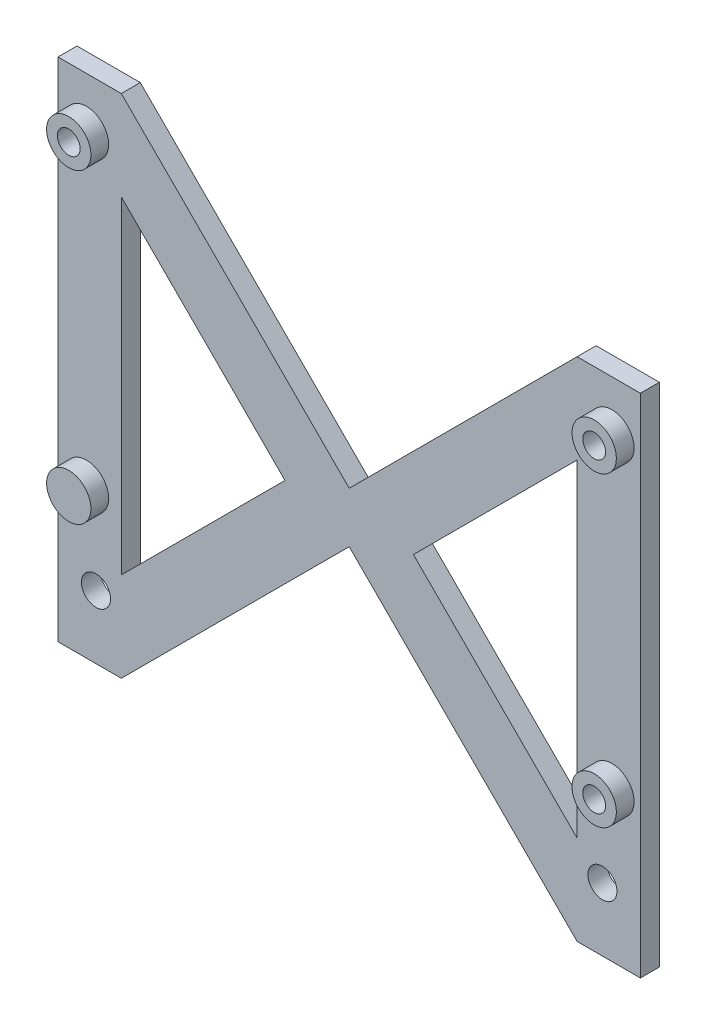
SolidWorks part; units mm, degrees
material "ABS"
ref_plane "Front Plane" through (0, 0, 0) normal (0, 0, 1) x (1, 0, 0)
ref_plane "Top Plane" through (0, 0, 0) normal (0, 1, 0) x (1, 0, 0)
ref_plane "Right Plane" through (0, 0, 0) normal (1, 0, 0) x (0, 0, -1)
sketch "Sketch1" plane through (0, 0, 0) normal (0, 0, 1) x (1, 0, 0)
  line L1 (-46, -40) -> (46, -40)
  line L2 (-46, -40) -> (-46, 40)
  line L3 (-46, 40) -> (46, 40)
  line L4 (46, -40) -> (46, 40)
  line L5 (-46, -40) -> (46, 40) construction
  line L6 (-46, 40) -> (46, -40) construction
  point P0 (0, 0)
  dimension "D1" = 92
  dimension "D2" = 80
extrude "Boss-Extrude1" add sketch "Sketch1" along normal blind 3
sketch "Sketch2" plane through (0, 0, 3) normal (0, 0, 1) x (1, 0, 0)
  line L0 (-36, 40) -> (0, 4)
  line L1 (46, 40) -> (-46, 40) construction
  line L2 (0, 4) -> (36, 40)
  line L3 (36, 40) -> (-36, 40)
  line L4 (-36, 25.8579) -> (-36, -25.8579)
  line L5 (-36, -25.8579) -> (-10.1421, 0)
  line L6 (-10.1421, 0) -> (-36, 25.8579)
  line L7 (-46, 40) -> (-46, -40) construction
  line L8 (46, -40) -> (46, 40) construction
  line L9 (-36, -40) -> (0, -4)
  line L10 (-46, -40) -> (46, -40) construction
  line L11 (0, -4) -> (36, -40)
  line L12 (36, -40) -> (-36, -40)
  line L14 (36, 25.8579) -> (36, -25.8579)
  line L15 (36, -25.8579) -> (10.1421, 0)
  line L16 (10.1421, 0) -> (36, 25.8579)
  dimension "D1" = 10
  dimension "D2" = 10
  dimension "D3" = 10
  dimension "D4" = 10
  dimension "D5" = 10
  dimension "D6" = 10
  dimension "D7" = 10
  dimension "D8" = 10
extrude "Cut-Extrude1" cut sketch "Sketch2" against normal through all
sketch "Sketch3" plane through (0, 0, 3) normal (0, 0, 1) x (1, 0, 0)
  line L0 (-46, 40) -> (-46, -40) construction
  line L1 (46, -40) -> (46, 40) construction
  line L2 (-36, 40) -> (-46, 40) construction
  circle A0 centre (-41.5, 32) radius 3.5
  circle A1 centre (-41.5, -16.4) radius 3.5
  circle A2 centre (41.5, -16.4) radius 3.5
  circle A3 centre (41.5, 32) radius 3.5
  dimension "D1" = 7
  dimension "D2" = 4.5
  dimension "D3" = 4.5
  dimension "D4" = 8
  dimension "D5" = 48.4
extrude "Boss-Extrude2" add sketch "Sketch3" along normal blind 2.8
sketch "Sketch4" plane through (0, 0, 5.8) normal (0, 0, 1) x (1, 0, 0)
  circle A0 centre (-41.5, 32) radius 1.8
  circle A1 centre (41.5, 32) radius 1.8
  circle A2 centre (41.5, -16.4) radius 1.8
  dimension "D1" = 3.6
extrude "Cut-Extrude2" cut sketch "Sketch4" against normal through all
sketch "Sketch5" plane through (0, 0, 3) normal (0, 0, 1) x (1, 0, 0)
  line L0 (-46, 40) -> (-46, -40) construction
  line L1 (-46, -40) -> (-36, -40) construction
  line L2 (46, -40) -> (46, 40) construction
  circle A0 centre (-40, -30) radius 2.3
  circle A1 centre (40, -30) radius 2.3
  dimension "D1" = 4.6
  dimension "D2" = 6
  dimension "D3" = 10
  dimension "D4" = 6
extrude "Cut-Extrude3" cut sketch "Sketch5" against normal through all
